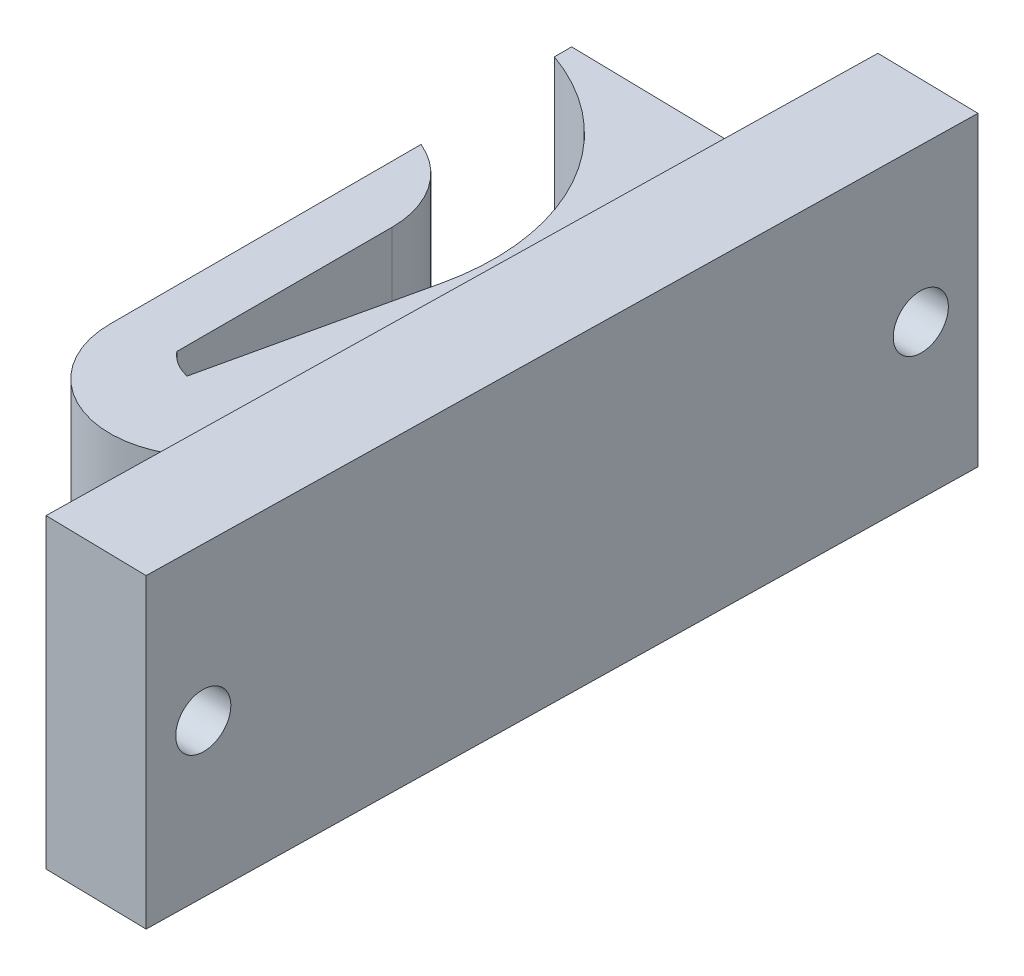
SolidWorks part; units mm, degrees
ref_plane "Front Plane" through (0, 0, 0) normal (0, 0, 1) x (1, 0, 0)
ref_plane "Top Plane" through (0, 0, 0) normal (0, 1, 0) x (1, 0, 0)
ref_plane "Right Plane" through (0, 0, 0) normal (1, 0, 0) x (0, 0, -1)
sketch "Sketch1" plane through (0, 0, 0) normal (0, 1, 0) x (1, 0, 0)
  line L0 (18.4245, -35.1774) -> (23.006, -14.8005)
  line L1 (15.8331, -33.5899) -> (15.8331, -12.488)
  line L10 (10.2279, -4.0485) -> (10.2279, -34.5269)
  line L11 (25.933, -41.2615) -> (26.9375, 11.2671)
  line L12 (26.9375, 11.2671) -> (9.3265, 11.6039)
  line L13 (9.3265, 11.6039) -> (9.3265, 9.9141)
  arc A2 (23.006, -14.8005) -> (9.3265, 9.9141) centre (2.2654, -10.1373) ccw
  arc A3 (18.4245, -35.1774) -> (15.8331, -33.5899) centre (19.4579, -30.5814) cw
  arc A4 (15.8331, -12.488) -> (10.2279, -4.0485) centre (6.677, -12.488) ccw
  arc A13 (10.2279, -34.5269) -> (25.933, -41.2615) centre (19.5244, -34.5269) ccw
  dimension "D2" = 21.2583
  dimension "D3" = 4.7107
  dimension "D4" = 9.156
  dimension "D5" = 2.2654
  dimension "D6" = 6.677
  dimension "D7" = 10.2279
  dimension "D8" = 18.4245
  dimension "D9" = 19.4579
extrude "Boss-Extrude1" add sketch "Sketch1" along normal blind 25
sketch "Sketch4" plane through (26.7123, 0, 0.5108) normal (0.9998, 0, 0.0191) x (0.0191, 0, -0.9998)
  line L1 (-55.7199, 27.3) -> (24.2801, 27.3)
  line L2 (-55.7199, 27.3) -> (-55.7199, -2.7)
  line L3 (-55.7199, -2.7) -> (24.2801, -2.7)
  line L4 (24.2801, 27.3) -> (24.2801, -2.7)
  line L5 (-55.7199, 27.3) -> (24.2801, -2.7) construction
  line L6 (-55.7199, -2.7) -> (24.2801, 27.3) construction
  line L12 (11.7801, 25) -> (11.7801, 0) construction
  line L13 (-40.7581, 25) -> (11.7801, 25) construction
  circle A0 centre (-50.2199, 12.3) radius 2.6511
  circle A1 centre (18.7801, 12.3) radius 2.6511
  point P0 (-15.7199, 12.3)
  point P7 (0, 0)
  point P8 (0, 0)
  point P15 (0, 0)
  point P16 (0, 0)
  point P17 (0, 0)
  dimension "D7" = 15
  dimension "D8" = 5.3021
  dimension "D1" = 30
  dimension "D2" = 80
  dimension "D3" = 12.5
  dimension "D4" = 2.3
  dimension "D5" = 5.5
  dimension "D6" = 5.5
extrude "Boss-Extrude4" add sketch "Sketch4" along normal blind 10
